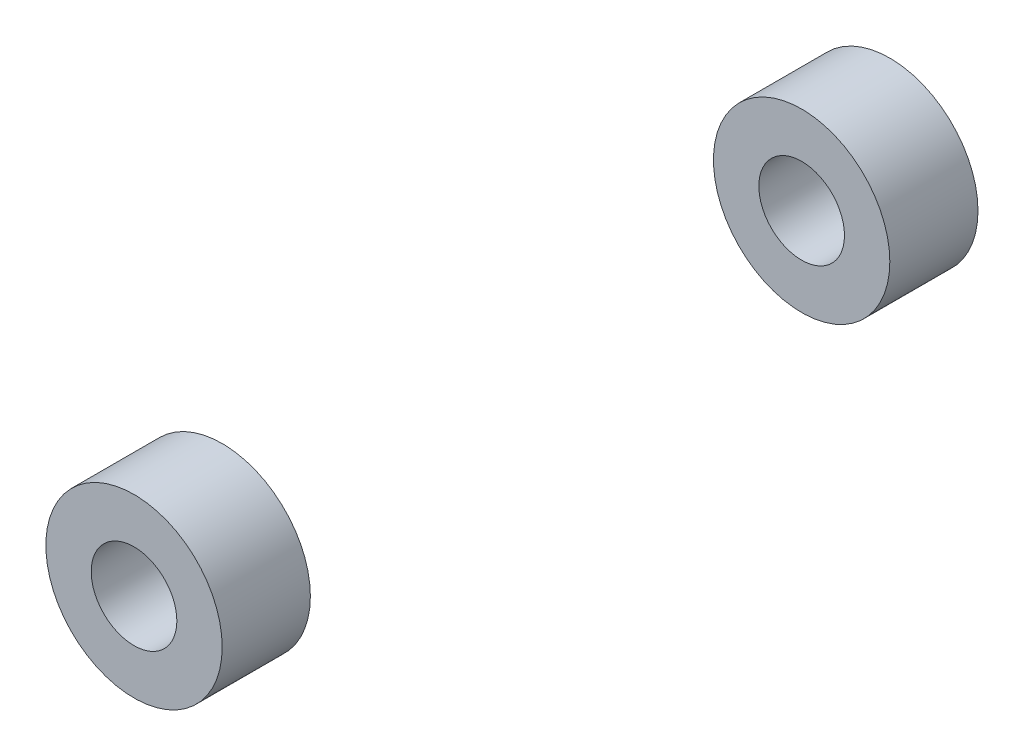
SolidWorks part; units mm, degrees
ref_plane "前视基准面" through (0, 0, 0) normal (0, 0, 1) x (1, 0, 0)
ref_plane "上视基准面" through (0, 0, 0) normal (0, 1, 0) x (1, 0, 0)
ref_plane "右视基准面" through (0, 0, 0) normal (1, 0, 0) x (0, 0, -1)
sketch "草图1" plane through (0, 0, 0) normal (0, 0, 1) x (1, 0, 0)
  circle A0 centre (0, 0) radius 3.5
  circle A1 centre (0, 0) radius 1.7
  dimension "D1" = 7
  dimension "D2" = 3.4
extrude "凸台-拉伸1" add sketch "草图1" along normal blind 30
ref_plane "基准面1" through (0, 0, 15) normal (0, 0, 1) x (1, 0, 0)
sketch "草图2" plane through (0, 0, 15) normal (0, 0, 1) x (1, 0, 0)
  circle A0 centre (0, 0) radius 3.5 construction
  circle A1 centre (0, 0) radius 3.5
extrude "切除-拉伸1" cut sketch "草图2" against normal mid plane 23
